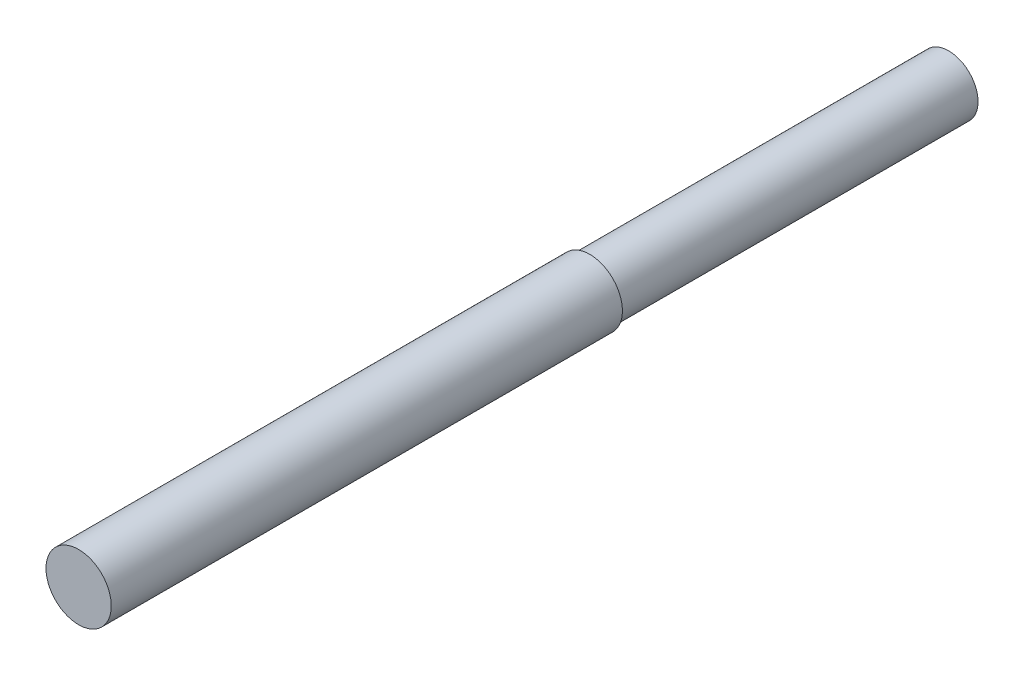
SolidWorks part; units mm, degrees
ref_plane "前视基准面" through (0, 0, 0) normal (0, 0, 1) x (1, 0, 0)
ref_plane "上视基准面" through (0, 0, 0) normal (0, 1, 0) x (1, 0, 0)
ref_plane "右视基准面" through (0, 0, 0) normal (1, 0, 0) x (0, 0, -1)
other "Configuration Table"
sketch "草图1" plane through (0, 0, 0) normal (0, 0, 1) x (1, 0, 0)
  circle A0 centre (0, 0) radius 30
extrude "凸台-拉伸1" add sketch "草图1" along normal blind 470
sketch "草图2" plane through (0, 0, 0) normal (0, 0, -1) x (-1, 0, 0)
  circle A0 centre (0, 0) radius 27
extrude "凸台-拉伸2" add sketch "草图2" along normal blind 330
